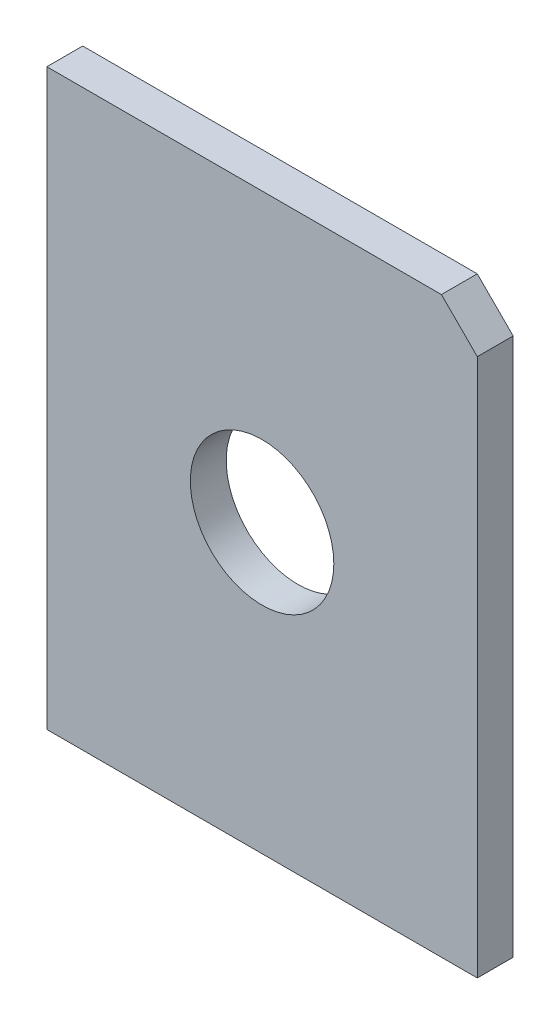
SolidWorks part; units mm, degrees
ref_plane "Front Plane" through (0, 0, 0) normal (0, 0, 1) x (1, 0, 0)
ref_plane "Top Plane" through (0, 0, 0) normal (0, 1, 0) x (1, 0, 0)
ref_plane "Right Plane" through (0, 0, 0) normal (1, 0, 0) x (0, 0, -1)
other "Configuration Table"
sketch "Sketch1" plane through (0, 0, 0) normal (0, 0, 1) x (1, 0, 0)
  line L0 (55, 80) -> (60, 75)
  line L1 (0, 0) -> (60, 0)
  line L2 (0, 0) -> (0, 80)
  line L3 (0, 80) -> (55, 80)
  line L4 (60, 0) -> (60, 75)
  circle A0 centre (30, 40) radius 10
  point P1 (60, 80)
extrude "Extrude1" add sketch "Sketch1" against normal blind 5
